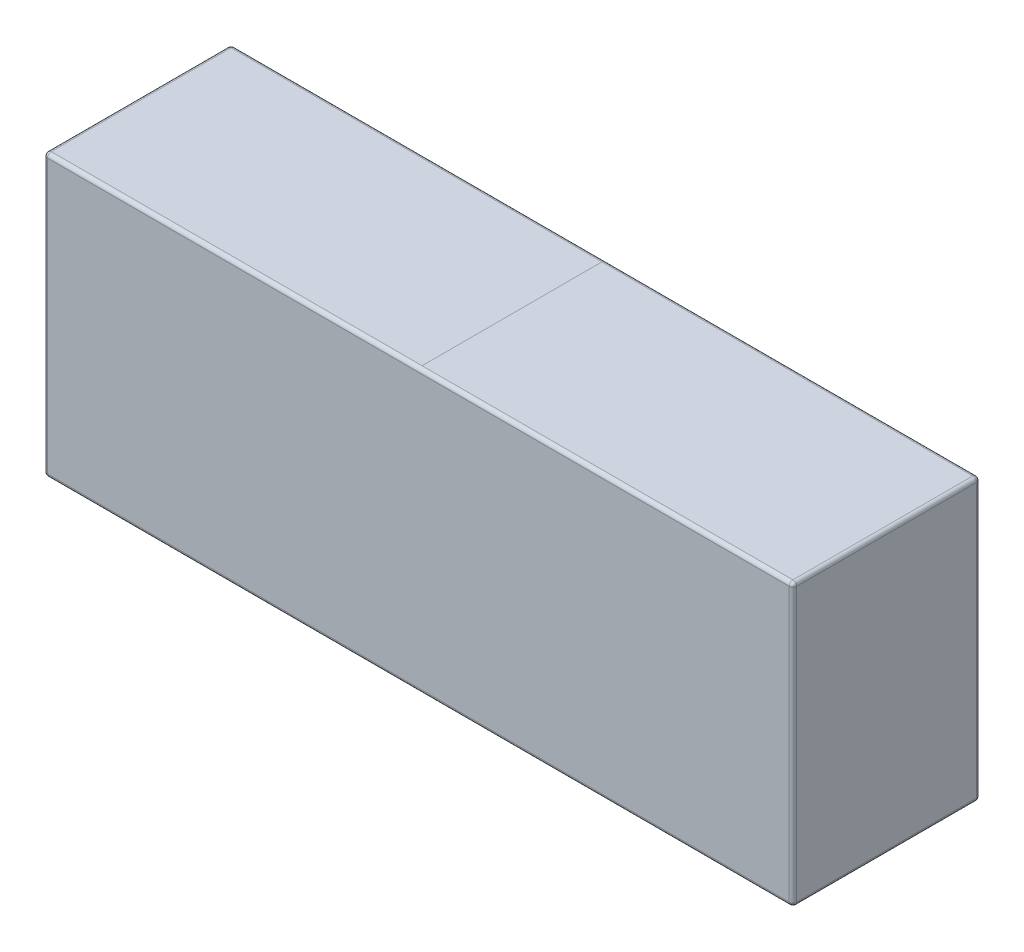
SolidWorks part; units mm, degrees
material "AISI 1020"
ref_plane "Alzado" through (0, 0, 0) normal (0, 0, 1) x (1, 0, 0)
ref_plane "Planta" through (0, 0, 0) normal (0, 1, 0) x (1, 0, 0)
ref_plane "Vista lateral" through (0, 0, 0) normal (1, 0, 0) x (0, 0, -1)
sketch "Croquis3" plane through (0, 0, 0) normal (0, 0, 1) x (1, 0, 0)
  line L1 (-20, 7.5) -> (20, 7.5)
  line L2 (-20, 7.5) -> (-20, -7.5)
  line L3 (-20, -7.5) -> (20, -7.5)
  line L4 (20, 7.5) -> (20, -7.5)
  line L5 (-20, 7.5) -> (20, -7.5) construction
  line L6 (-20, -7.5) -> (20, 7.5) construction
  point P0 (0, 0)
  dimension "D1" = 15
  dimension "D2" = 40
extrude "Saliente-Extruir1" add sketch "Croquis3" along normal blind 10
fillet "Redondeo1" radius 0.2 12 edges at (-20, -7.5, 5) (-20, 0, 0) (0, -7.5, 0) (20, -7.5, 5) (20, 0, 0) (0, -7.5, 10) (-20, 0, 10) (20, 0, 10) (20, 7.5, 5) (0, 7.5, 10) (-20, 7.5, 5) (0, 7.5, 0)
sketch "Croquis4" plane through (0, 7.5, 0) normal (0, 1, 0) x (1, 0, 0)
  line L0 (0, -0.2) -> (0, -9.8)
  line L1 (19.8, -0.2) -> (-19.8, -0.2) construction
  line L2 (-19.8, -9.8) -> (19.8, -9.8) construction
split line "Línea de partición1"
